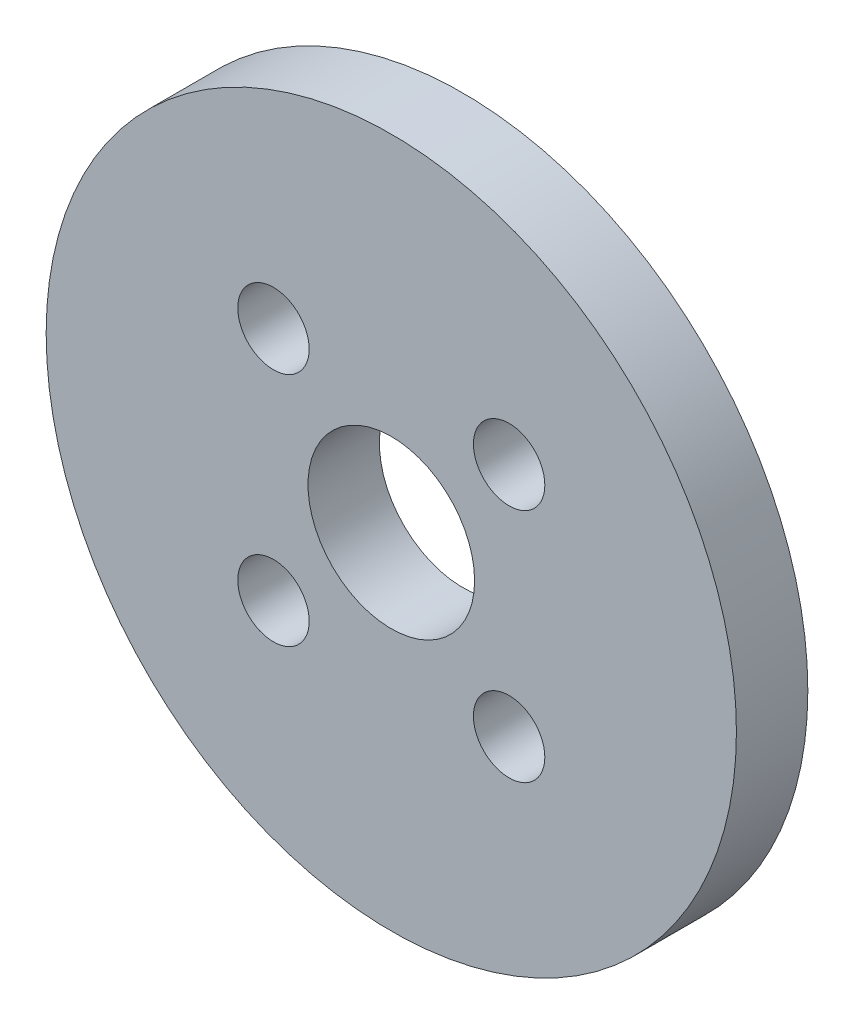
SolidWorks part; units mm, degrees
material "AISI 1020"
ref_plane "Front Plane" through (0, 0, 0) normal (0, 0, 1) x (1, 0, 0)
ref_plane "Top Plane" through (0, 0, 0) normal (0, 1, 0) x (1, 0, 0)
ref_plane "Right Plane" through (0, 0, 0) normal (1, 0, 0) x (0, 0, -1)
sketch "Sketch1" plane through (0, 0, 0) normal (0, 0, 1) x (1, 0, 0)
  line L1 (-10.9545, -9.5) -> (10.9545, -9.5) construction
  line L2 (-10.9545, -9.5) -> (-10.9545, 9.5) construction
  line L3 (-10.9545, 9.5) -> (10.9545, 9.5) construction
  line L4 (10.9545, -9.5) -> (10.9545, 9.5) construction
  line L5 (-10.9545, -9.5) -> (10.9545, 9.5) construction
  line L6 (-10.9545, 9.5) -> (10.9545, -9.5) construction
  line L7 (-4.9497, -4.9497) -> (4.9497, -4.9497) construction
  line L8 (-4.9497, -4.9497) -> (-4.9497, 4.9497) construction
  line L9 (-4.9497, 4.9497) -> (4.9497, 4.9497) construction
  line L10 (4.9497, -4.9497) -> (4.9497, 4.9497) construction
  line L11 (-4.9497, -4.9497) -> (4.9497, 4.9497) construction
  line L12 (-4.9497, 4.9497) -> (4.9497, -4.9497) construction
  circle A0 centre (0, 0) radius 3.5
  circle A1 centre (0, 0) radius 14.5
  circle A3 centre (-4.9497, 4.9497) radius 1.5
  circle A4 centre (4.9497, 4.9497) radius 1.5
  circle A5 centre (4.9497, -4.9497) radius 1.5
  circle A6 centre (-4.9497, -4.9497) radius 1.5
  dimension "D1" = 7
  dimension "D2" = 29
  dimension "D3" = 3
  dimension "D4" = 14
  dimension "D5" = 19
extrude "Boss-Extrude1" add sketch "Sketch1" along normal blind 3 contours L1 A1 A6 A5 A4 A3 A0
